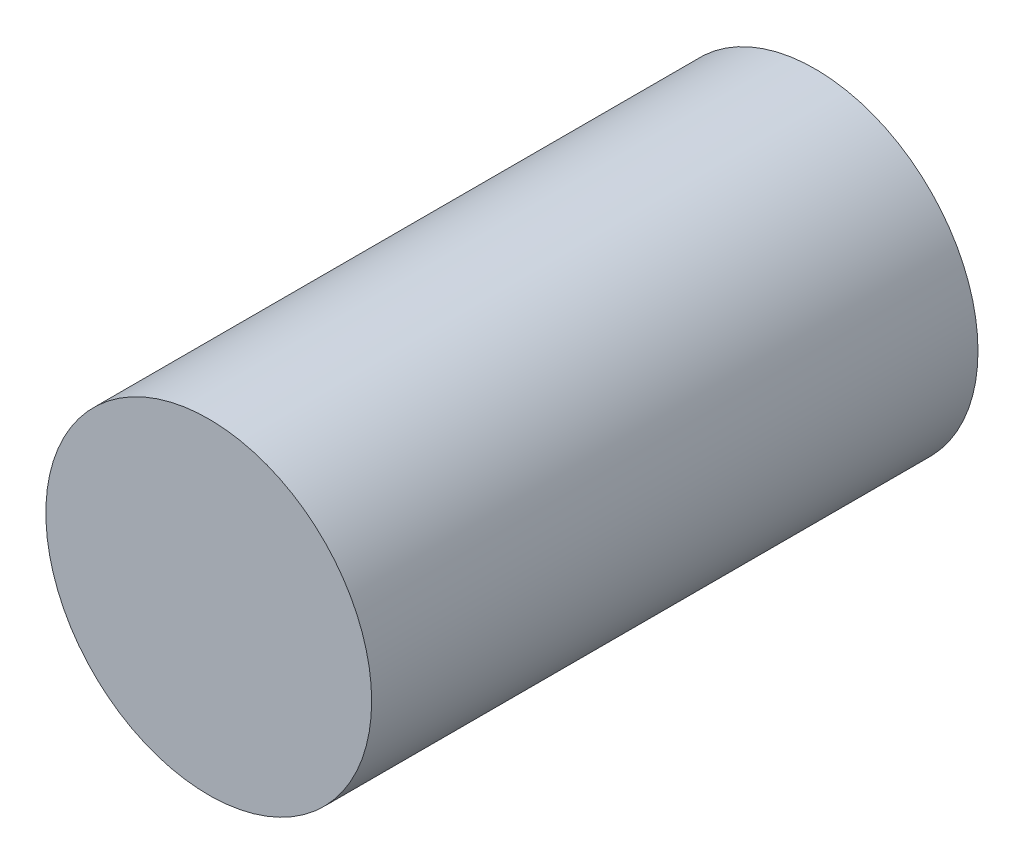
SolidWorks part; units mm, degrees
ref_plane "Front Plane" through (0, 0, 0) normal (0, 0, 1) x (1, 0, 0)
ref_plane "Top Plane" through (0, 0, 0) normal (0, 1, 0) x (1, 0, 0)
ref_plane "Right Plane" through (0, 0, 0) normal (1, 0, 0) x (0, 0, -1)
sketch "Sketch1" plane through (0, 0, 0) normal (0, 0, 1) x (1, 0, 0)
  circle A0 centre (0, 0) radius 18
  dimension "D1" = 36
extrude "Boss-Extrude1" add sketch "Sketch1" along normal blind 67
